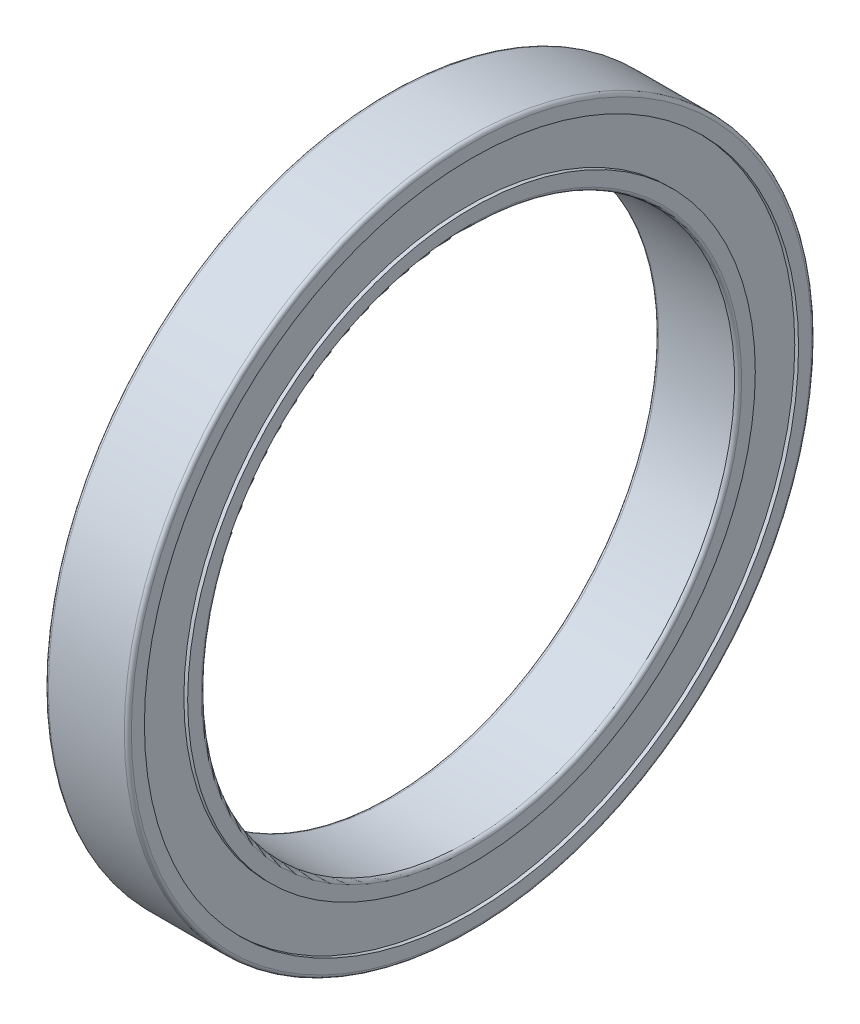
SolidWorks part; units mm, degrees
material "炭素鋼(普通)"
ref_plane "Front Plane" through (0, 0, 0) normal (0, 0, 1) x (1, 0, 0)
ref_plane "Top Plane" through (0, 0, 0) normal (0, 1, 0) x (1, 0, 0)
ref_plane "Right Plane" through (0, 0, 0) normal (1, 0, 0) x (0, 0, -1)
sketch "Sketch1" plane through (0, 0, 0) normal (0, 0, 1) x (1, 0, 0)
  line L0 (0, 0) -> (7, 0) construction
  line L1 (0, 22.5) -> (7, 22.5)
  line L2 (0, 29) -> (7, 29)
  line L3 (0, 29) -> (0, 27.6)
  line L4 (0, 27.6) -> (0.32, 27.6)
  line L5 (7, 29) -> (7, 27.6)
  line L6 (0.32, 27.6) -> (0.32, 23.95)
  line L7 (0.32, 23.95) -> (0, 23.95)
  line L8 (0, 23.95) -> (0, 22.5)
  line L9 (7, 27.6) -> (6.68, 27.6)
  line L10 (6.68, 27.6) -> (6.68, 23.95)
  line L11 (6.68, 23.95) -> (7, 23.95)
  line L12 (7, 23.95) -> (7, 22.5)
  dimension "D" = 58
  dimension "B" = 7
  dimension "D_s" = 45
  dimension "MSM_1" = 55.2
  dimension "MSM_2" = 47.9
  dimension "MSM_3" = 0.32
revolve "Revolve1" add sketch "Sketch1" angle 360 about L0
fillet "Fillet1" radius 0.3 2 edges at (7, 0, 29) (0, 0, 29)
fillet "Fillet2" radius 0.3 2 edges at (7, 0, 22.5) (0, 0, 22.5)
